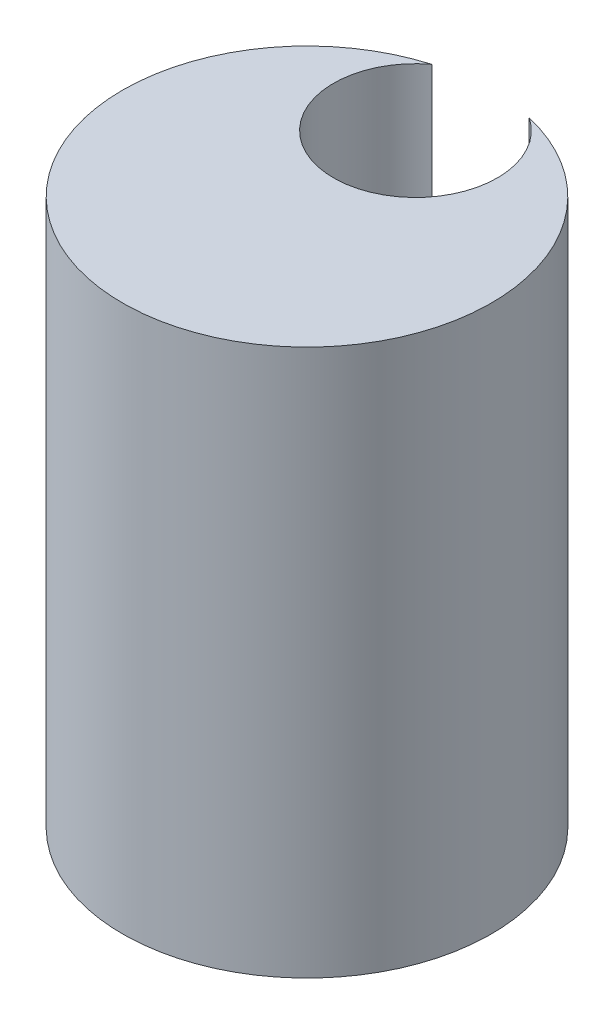
SolidWorks part; units mm, degrees
ref_plane "前视基准面" through (0, 0, 0) normal (0, 0, 1) x (1, 0, 0)
ref_plane "上视基准面" through (0, 0, 0) normal (0, 1, 0) x (1, 0, 0)
ref_plane "右视基准面" through (0, 0, 0) normal (1, 0, 0) x (0, 0, -1)
other "Configuration Table"
sketch "草图1" plane through (0, 0, 0) normal (0, 1, 0) x (1, 0, 0)
  circle A1 centre (0, 0) radius 1.35
  point P0 (0, 0)
  point P5 (0, 0)
  dimension "D1" = 2.7
extrude "凸台-拉伸1" add sketch "草图1" along normal blind 4
sketch "草图2" plane through (0, 4, 0) normal (0, 1, 0) x (1, 0, 0)
  circle A0 centre (-0.0213, 0.8152) radius 0.6
  point P2 (0, 0)
  point P3 (0, 0)
  dimension "D1" = 1.2
extrude "切除-拉伸1" cut sketch "草图2" against normal through all
